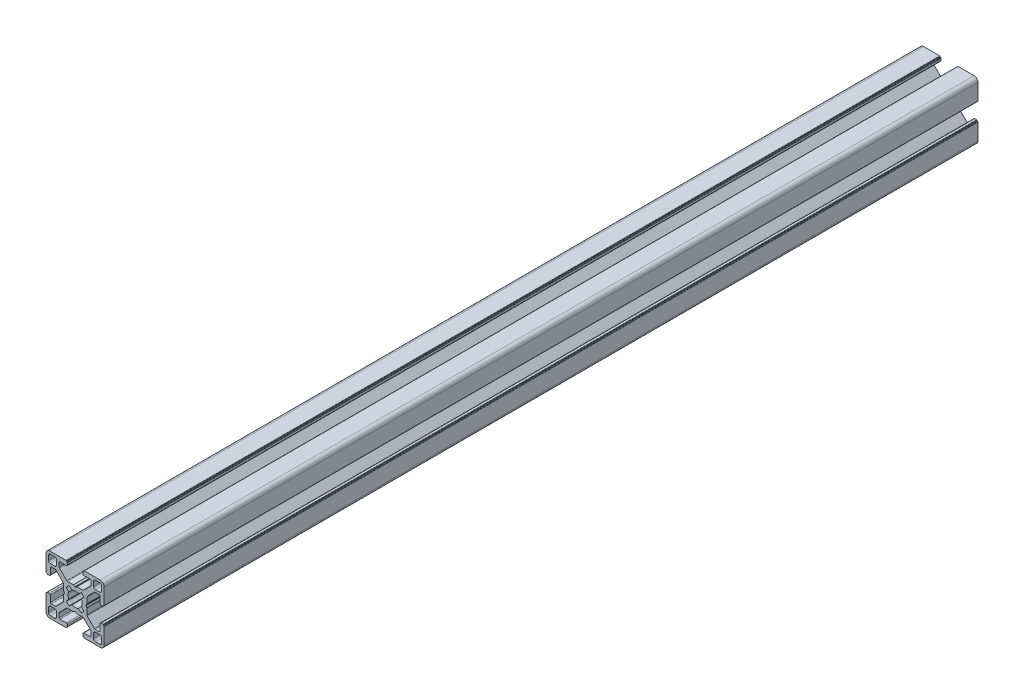
SolidWorks part; units mm, degrees
ref_plane "Alzado" through (0, 0, 0) normal (0, 0, 1) x (1, 0, 0)
ref_plane "Planta" through (0, 0, 0) normal (0, 1, 0) x (1, 0, 0)
ref_plane "Vista lateral" through (0, 0, 0) normal (1, 0, 0) x (0, 0, -1)
ref_plane "Plano1" through (0, 0, 1000) normal (0, 0, 1) x (1, 0, 0)
sketch "Croquis1" plane through (0, 0, 1000) normal (0, 0, 1) x (1, 0, 0)
  line L0 (8, -5.5) -> (5.8, -5.5)
  line L1 (4.8, -4.5) -> (4.8, -2.3)
  line L2 (5.8, -1.3) -> (8, -1.3)
  line L3 (9, -2.3) -> (9, -4.5)
  line L4 (-15.2, -5.5) -> (-17.4, -5.5)
  line L5 (-18.4, -4.5) -> (-18.4, -2.3)
  line L6 (-17.4, -1.3) -> (-15.2, -1.3)
  line L7 (-14.2, -2.3) -> (-14.2, -4.5)
  line L8 (-17.4, -24.5) -> (-15.2, -24.5)
  line L9 (-14.2, -25.5) -> (-14.2, -27.7)
  line L10 (-15.2, -28.7) -> (-17.4, -28.7)
  line L11 (-18.4, -27.7) -> (-18.4, -25.5)
  line L12 (5.8, -24.5) -> (8, -24.5)
  line L13 (9, -25.5) -> (9, -27.7)
  line L14 (8, -28.7) -> (5.8, -28.7)
  line L15 (4.8, -27.7) -> (4.8, -25.5)
  line L16 (-7.8359, -10.4816) -> (-6.3001, -11.7194)
  line L17 (-3.0999, -11.7194) -> (-1.5641, -10.4816)
  line L18 (-0.1947, -11.8453) -> (-1.4194, -13.3999)
  line L19 (-1.4194, -16.6001) -> (-0.1947, -18.1547)
  line L20 (-1.5641, -19.5184) -> (-3.0999, -18.2806)
  line L21 (-6.3001, -18.2806) -> (-7.8359, -19.5184)
  line L22 (-9.2053, -18.1547) -> (-7.9806, -16.6001)
  line L23 (-7.9806, -13.3999) -> (-9.2053, -11.8453)
  line L24 (9.8, -10.5) -> (10.1, -10.5)
  line L25 (10.3, -10.3) -> (10.3, -2)
  line L26 (8.3, 0) -> (0, 0)
  line L27 (-0.2, -0.2) -> (-0.2, -0.5)
  line L28 (-0.2, -0.5) -> (-0.5, -0.5)
  line L29 (-0.7, -0.7) -> (-0.7, -1.7)
  line L30 (-0.2, -2.2) -> (3.05, -2.2)
  line L31 (3.55, -2.7) -> (3.55, -4.7431)
  line L32 (3.4037, -5.0964) -> (-0.3491, -8.8534)
  line L33 (-0.7028, -9) -> (-3.7468, -9)
  line L34 (-3.8462, -9.0264) -> (-4.6006, -9.4583)
  line L35 (-4.7994, -9.4583) -> (-5.5538, -9.0264)
  line L36 (-5.6532, -9) -> (-8.6972, -9)
  line L37 (-9.0509, -8.8534) -> (-12.8037, -5.0964)
  line L38 (-12.95, -4.7431) -> (-12.95, -2.7)
  line L39 (-12.45, -2.2) -> (-9.2, -2.2)
  line L40 (-8.7, -1.7) -> (-8.7, -0.7)
  line L41 (-8.9, -0.5) -> (-9.2, -0.5)
  line L42 (-9.2, -0.5) -> (-9.2, -0.2)
  line L43 (-9.4, 0) -> (-17.7, 0)
  line L44 (-19.7, -2) -> (-19.7, -10.3)
  line L45 (-19.5, -10.5) -> (-19.2, -10.5)
  line L46 (-19.2, -10.5) -> (-19.2, -10.8)
  line L47 (-19, -11) -> (-18, -11)
  line L48 (-17.5, -10.5) -> (-17.5, -7.25)
  line L49 (-17, -6.75) -> (-14.9569, -6.75)
  line L50 (-14.6036, -6.8963) -> (-10.8466, -10.6491)
  line L51 (-10.7, -11.0028) -> (-10.7, -14.0468)
  line L52 (-10.6736, -14.1462) -> (-10.2417, -14.9006)
  line L53 (-10.2417, -15.0994) -> (-10.6736, -15.8538)
  line L54 (-10.7, -15.9532) -> (-10.7, -18.9972)
  line L55 (-10.8466, -19.3509) -> (-14.6036, -23.1037)
  line L56 (-14.9569, -23.25) -> (-17, -23.25)
  line L57 (-17.5, -22.75) -> (-17.5, -19.5)
  line L58 (-18, -19) -> (-19, -19)
  line L59 (-19.2, -19.2) -> (-19.2, -19.5)
  line L60 (-19.2, -19.5) -> (-19.5, -19.5)
  line L61 (-19.7, -19.7) -> (-19.7, -28)
  line L62 (-17.7, -30) -> (-9.4, -30)
  line L63 (-9.2, -29.8) -> (-9.2, -29.5)
  line L64 (-9.2, -29.5) -> (-8.9, -29.5)
  line L65 (-8.7, -29.3) -> (-8.7, -28.3)
  line L66 (-9.2, -27.8) -> (-12.45, -27.8)
  line L67 (-12.95, -27.3) -> (-12.95, -25.2569)
  line L68 (-12.8037, -24.9036) -> (-9.0509, -21.1466)
  line L69 (-8.6972, -21) -> (-5.6532, -21)
  line L70 (-5.5538, -20.9736) -> (-4.7994, -20.5417)
  line L71 (-4.6006, -20.5417) -> (-3.8462, -20.9736)
  line L72 (-3.7468, -21) -> (-0.7028, -21)
  line L73 (-0.3491, -21.1466) -> (3.4037, -24.9036)
  line L74 (3.55, -25.2569) -> (3.55, -27.3)
  line L75 (3.05, -27.8) -> (-0.2, -27.8)
  line L76 (-0.7, -28.3) -> (-0.7, -29.3)
  line L77 (-0.5, -29.5) -> (-0.2, -29.5)
  line L78 (-0.2, -29.5) -> (-0.2, -29.8)
  line L79 (0, -30) -> (8.3, -30)
  line L80 (10.3, -28) -> (10.3, -19.7)
  line L81 (10.1, -19.5) -> (9.8, -19.5)
  line L82 (9.8, -19.5) -> (9.8, -19.2)
  line L83 (9.6, -19) -> (8.6, -19)
  line L84 (8.1, -19.5) -> (8.1, -22.75)
  line L85 (7.6, -23.25) -> (5.5569, -23.25)
  line L86 (5.2036, -23.1037) -> (1.4466, -19.3509)
  line L87 (1.3, -18.9972) -> (1.3, -15.9532)
  line L88 (1.2736, -15.8538) -> (0.8417, -15.0994)
  line L89 (0.8417, -14.9006) -> (1.2736, -14.1462)
  line L90 (1.3, -14.0468) -> (1.3, -11.0028)
  line L91 (1.4466, -10.6491) -> (5.2036, -6.8963)
  line L92 (5.5569, -6.75) -> (7.6, -6.75)
  line L93 (8.1, -7.25) -> (8.1, -10.5)
  line L94 (8.6, -11) -> (9.6, -11)
  line L95 (9.8, -10.8) -> (9.8, -10.5)
  arc A0 (9, -4.5) -> (8, -5.5) centre (8, -4.5) cw
  arc A1 (5.8, -5.5) -> (4.8, -4.5) centre (5.8, -4.5) cw
  arc A2 (4.8, -2.3) -> (5.8, -1.3) centre (5.8, -2.3) cw
  arc A3 (8, -1.3) -> (9, -2.3) centre (8, -2.3) cw
  arc A4 (-14.2, -4.5) -> (-15.2, -5.5) centre (-15.2, -4.5) cw
  arc A5 (-17.4, -5.5) -> (-18.4, -4.5) centre (-17.4, -4.5) cw
  arc A6 (-18.4, -2.3) -> (-17.4, -1.3) centre (-17.4, -2.3) cw
  arc A7 (-15.2, -1.3) -> (-14.2, -2.3) centre (-15.2, -2.3) cw
  arc A8 (-18.4, -25.5) -> (-17.4, -24.5) centre (-17.4, -25.5) cw
  arc A9 (-15.2, -24.5) -> (-14.2, -25.5) centre (-15.2, -25.5) cw
  arc A10 (-14.2, -27.7) -> (-15.2, -28.7) centre (-15.2, -27.7) cw
  arc A11 (-17.4, -28.7) -> (-18.4, -27.7) centre (-17.4, -27.7) cw
  arc A12 (4.8, -25.5) -> (5.8, -24.5) centre (5.8, -25.5) cw
  arc A13 (8, -24.5) -> (9, -25.5) centre (8, -25.5) cw
  arc A14 (9, -27.7) -> (8, -28.7) centre (8, -27.7) cw
  arc A15 (5.8, -28.7) -> (4.8, -27.7) centre (5.8, -27.7) cw
  arc A16 (-9.2053, -11.8453) -> (-7.8359, -10.4816) centre (-4.7, -15) cw
  arc A17 (-6.3001, -11.7194) -> (-3.0999, -11.7194) centre (-4.7, -15) cw
  arc A18 (-1.5641, -10.4816) -> (-0.1947, -11.8453) centre (-4.7, -15) cw
  arc A19 (-1.4194, -13.3999) -> (-1.4194, -16.6001) centre (-4.7, -15) cw
  arc A20 (-0.1947, -18.1547) -> (-1.5641, -19.5184) centre (-4.7, -15) cw
  arc A21 (-3.0999, -18.2806) -> (-6.3001, -18.2806) centre (-4.7, -15) cw
  arc A22 (-7.8359, -19.5184) -> (-9.2053, -18.1547) centre (-4.7, -15) cw
  arc A23 (-7.9806, -16.6001) -> (-7.9806, -13.3999) centre (-4.7, -15) cw
  arc A24 (10.1, -10.5) -> (10.3, -10.3) centre (10.1, -10.3) ccw
  arc A25 (10.3, -2) -> (8.3, 0) centre (8.3, -2) ccw
  arc A26 (0, 0) -> (-0.2, -0.2) centre (0, -0.2) ccw
  arc A27 (-0.5, -0.5) -> (-0.7, -0.7) centre (-0.5, -0.7) ccw
  arc A28 (-0.7, -1.7) -> (-0.2, -2.2) centre (-0.2, -1.7) ccw
  arc A29 (3.05, -2.2) -> (3.55, -2.7) centre (3.05, -2.7) cw
  arc A30 (3.55, -4.7431) -> (3.4037, -5.0964) centre (3.05, -4.7431) cw
  arc A31 (-0.3491, -8.8534) -> (-0.7028, -9) centre (-0.7028, -8.5) cw
  arc A32 (-3.7468, -9) -> (-3.8462, -9.0264) centre (-3.7468, -9.2) ccw
  arc A33 (-4.6006, -9.4583) -> (-4.7994, -9.4583) centre (-4.7, -9.2847) cw
  arc A34 (-5.5538, -9.0264) -> (-5.6532, -9) centre (-5.6532, -9.2) ccw
  arc A35 (-8.6972, -9) -> (-9.0509, -8.8534) centre (-8.6972, -8.5) cw
  arc A36 (-12.8037, -5.0964) -> (-12.95, -4.7431) centre (-12.45, -4.7431) cw
  arc A37 (-12.95, -2.7) -> (-12.45, -2.2) centre (-12.45, -2.7) cw
  arc A38 (-9.2, -2.2) -> (-8.7, -1.7) centre (-9.2, -1.7) ccw
  arc A39 (-8.7, -0.7) -> (-8.9, -0.5) centre (-8.9, -0.7) ccw
  arc A40 (-9.2, -0.2) -> (-9.4, 0) centre (-9.4, -0.2) ccw
  arc A41 (-17.7, 0) -> (-19.7, -2) centre (-17.7, -2) ccw
  arc A42 (-19.7, -10.3) -> (-19.5, -10.5) centre (-19.5, -10.3) ccw
  arc A43 (-19.2, -10.8) -> (-19, -11) centre (-19, -10.8) ccw
  arc A44 (-18, -11) -> (-17.5, -10.5) centre (-18, -10.5) ccw
  arc A45 (-17.5, -7.25) -> (-17, -6.75) centre (-17, -7.25) cw
  arc A46 (-14.9569, -6.75) -> (-14.6036, -6.8963) centre (-14.9569, -7.25) cw
  arc A47 (-10.8466, -10.6491) -> (-10.7, -11.0028) centre (-11.2, -11.0028) cw
  arc A48 (-10.7, -14.0468) -> (-10.6736, -14.1462) centre (-10.5, -14.0468) ccw
  arc A49 (-10.2417, -14.9006) -> (-10.2417, -15.0994) centre (-10.4153, -15) cw
  arc A50 (-10.6736, -15.8538) -> (-10.7, -15.9532) centre (-10.5, -15.9532) ccw
  arc A51 (-10.7, -18.9972) -> (-10.8466, -19.3509) centre (-11.2, -18.9972) cw
  arc A52 (-14.6036, -23.1037) -> (-14.9569, -23.25) centre (-14.9569, -22.75) cw
  arc A53 (-17, -23.25) -> (-17.5, -22.75) centre (-17, -22.75) cw
  arc A54 (-17.5, -19.5) -> (-18, -19) centre (-18, -19.5) ccw
  arc A55 (-19, -19) -> (-19.2, -19.2) centre (-19, -19.2) ccw
  arc A56 (-19.5, -19.5) -> (-19.7, -19.7) centre (-19.5, -19.7) ccw
  arc A57 (-19.7, -28) -> (-17.7, -30) centre (-17.7, -28) ccw
  arc A58 (-9.4, -30) -> (-9.2, -29.8) centre (-9.4, -29.8) ccw
  arc A59 (-8.9, -29.5) -> (-8.7, -29.3) centre (-8.9, -29.3) ccw
  arc A60 (-8.7, -28.3) -> (-9.2, -27.8) centre (-9.2, -28.3) ccw
  arc A61 (-12.45, -27.8) -> (-12.95, -27.3) centre (-12.45, -27.3) cw
  arc A62 (-12.95, -25.2569) -> (-12.8037, -24.9036) centre (-12.45, -25.2569) cw
  arc A63 (-9.0509, -21.1466) -> (-8.6972, -21) centre (-8.6972, -21.5) cw
  arc A64 (-5.6532, -21) -> (-5.5538, -20.9736) centre (-5.6532, -20.8) ccw
  arc A65 (-4.7994, -20.5417) -> (-4.6006, -20.5417) centre (-4.7, -20.7153) cw
  arc A66 (-3.8462, -20.9736) -> (-3.7468, -21) centre (-3.7468, -20.8) ccw
  arc A67 (-0.7028, -21) -> (-0.3491, -21.1466) centre (-0.7028, -21.5) cw
  arc A68 (3.4037, -24.9036) -> (3.55, -25.2569) centre (3.05, -25.2569) cw
  arc A69 (3.55, -27.3) -> (3.05, -27.8) centre (3.05, -27.3) cw
  arc A70 (-0.2, -27.8) -> (-0.7, -28.3) centre (-0.2, -28.3) ccw
  arc A71 (-0.7, -29.3) -> (-0.5, -29.5) centre (-0.5, -29.3) ccw
  arc A72 (-0.2, -29.8) -> (0, -30) centre (0, -29.8) ccw
  arc A73 (8.3, -30) -> (10.3, -28) centre (8.3, -28) ccw
  arc A74 (10.3, -19.7) -> (10.1, -19.5) centre (10.1, -19.7) ccw
  arc A75 (9.8, -19.2) -> (9.6, -19) centre (9.6, -19.2) ccw
  arc A76 (8.6, -19) -> (8.1, -19.5) centre (8.6, -19.5) ccw
  arc A77 (8.1, -22.75) -> (7.6, -23.25) centre (7.6, -22.75) cw
  arc A78 (5.5569, -23.25) -> (5.2036, -23.1037) centre (5.5569, -22.75) cw
  arc A79 (1.4466, -19.3509) -> (1.3, -18.9972) centre (1.8, -18.9972) cw
  arc A80 (1.3, -15.9532) -> (1.2736, -15.8538) centre (1.1, -15.9532) ccw
  arc A81 (0.8417, -15.0994) -> (0.8417, -14.9006) centre (1.0153, -15) cw
  arc A82 (1.2736, -14.1462) -> (1.3, -14.0468) centre (1.1, -14.0468) ccw
  arc A83 (1.3, -11.0028) -> (1.4466, -10.6491) centre (1.8, -11.0028) cw
  arc A84 (5.2036, -6.8963) -> (5.5569, -6.75) centre (5.5569, -7.25) cw
  arc A85 (7.6, -6.75) -> (8.1, -7.25) centre (7.6, -7.25) cw
  arc A86 (8.1, -10.5) -> (8.6, -11) centre (8.6, -10.5) ccw
  arc A87 (9.6, -11) -> (9.8, -10.8) centre (9.6, -10.8) ccw
extrude "Saliente-Extruir1" add sketch "Croquis1" against normal blind 1000
sketch "Croquis4" plane through (0, 0, 0) normal (0, 0, -1) x (-1, 0, 0)
  line L72 (-9.8, -10.5) -> (-9.8, -10.8)
  line L73 (-9.6, -11) -> (-8.6, -11)
  line L74 (-8.1, -10.5) -> (-8.1, -7.25)
  line L75 (-7.6, -6.75) -> (-5.5569, -6.75)
  line L76 (-5.2036, -6.8963) -> (-1.4466, -10.6491)
  line L77 (-1.3, -11.0028) -> (-1.3, -14.0468)
  line L78 (-1.2736, -14.1462) -> (-0.8417, -14.9006)
  line L79 (-0.8417, -15.0994) -> (-1.2736, -15.8538)
  line L80 (-1.3, -15.9532) -> (-1.3, -18.9972)
  line L81 (-1.4466, -19.3509) -> (-5.2036, -23.1037)
  line L82 (-5.5569, -23.25) -> (-7.6, -23.25)
  line L83 (-8.1, -22.75) -> (-8.1, -19.5)
  line L84 (-8.6, -19) -> (-9.6, -19)
  line L85 (-9.8, -19.2) -> (-9.8, -19.5)
  line L86 (-9.8, -19.5) -> (-10.1, -19.5)
  line L87 (-10.3, -19.7) -> (-10.3, -28)
  line L88 (-8.3, -30) -> (0, -30)
  line L89 (0.2, -29.8) -> (0.2, -29.5)
  line L90 (0.2, -29.5) -> (0.5, -29.5)
  line L91 (0.7, -29.3) -> (0.7, -28.3)
  line L92 (0.2, -27.8) -> (-3.05, -27.8)
  line L93 (-3.55, -27.3) -> (-3.55, -25.2569)
  line L94 (-3.4037, -24.9036) -> (0.3491, -21.1466)
  line L95 (0.7028, -21) -> (3.7468, -21)
  line L96 (3.8462, -20.9736) -> (4.6006, -20.5417)
  line L97 (4.7994, -20.5417) -> (5.5538, -20.9736)
  line L98 (5.6532, -21) -> (8.6972, -21)
  line L99 (9.0509, -21.1466) -> (12.8037, -24.9036)
  line L100 (12.95, -25.2569) -> (12.95, -27.3)
  line L101 (12.45, -27.8) -> (9.2, -27.8)
  line L102 (8.7, -28.3) -> (8.7, -29.3)
  line L103 (8.9, -29.5) -> (9.2, -29.5)
  line L104 (9.2, -29.5) -> (9.2, -29.8)
  line L105 (9.4, -30) -> (17.7, -30)
  line L106 (19.7, -28) -> (19.7, -19.7)
  line L107 (19.5, -19.5) -> (19.2, -19.5)
  line L108 (19.2, -19.5) -> (19.2, -19.2)
  line L109 (19, -19) -> (18, -19)
  line L110 (17.5, -19.5) -> (17.5, -22.75)
  line L111 (17, -23.25) -> (14.9569, -23.25)
  line L112 (14.6036, -23.1037) -> (10.8466, -19.3509)
  line L113 (10.7, -18.9972) -> (10.7, -15.9532)
  line L114 (10.6736, -15.8538) -> (10.2417, -15.0994)
  line L115 (10.2417, -14.9006) -> (10.6736, -14.1462)
  line L116 (10.7, -14.0468) -> (10.7, -11.0028)
  line L117 (10.8466, -10.6491) -> (14.6036, -6.8963)
  line L118 (14.9569, -6.75) -> (17, -6.75)
  line L119 (17.5, -7.25) -> (17.5, -10.5)
  line L120 (18, -11) -> (19, -11)
  line L121 (19.2, -10.8) -> (19.2, -10.5)
  line L122 (19.2, -10.5) -> (19.5, -10.5)
  line L123 (19.7, -10.3) -> (19.7, -2)
  line L124 (17.7, 0) -> (9.4, 0)
  line L125 (9.2, -0.2) -> (9.2, -0.5)
  line L126 (9.2, -0.5) -> (8.9, -0.5)
  line L127 (8.7, -0.7) -> (8.7, -1.7)
  line L128 (9.2, -2.2) -> (12.45, -2.2)
  line L129 (12.95, -2.7) -> (12.95, -4.7431)
  line L130 (12.8037, -5.0964) -> (9.0509, -8.8534)
  line L131 (8.6972, -9) -> (5.6532, -9)
  line L132 (5.5538, -9.0264) -> (4.7994, -9.4583)
  line L133 (4.6006, -9.4583) -> (3.8462, -9.0264)
  line L134 (3.7468, -9) -> (0.7028, -9)
  line L135 (0.3491, -8.8534) -> (-3.4037, -5.0964)
  line L136 (-3.55, -4.7431) -> (-3.55, -2.7)
  line L137 (-3.05, -2.2) -> (0.2, -2.2)
  line L138 (0.7, -1.7) -> (0.7, -0.7)
  line L139 (0.5, -0.5) -> (0.2, -0.5)
  line L140 (0.2, -0.5) -> (0.2, -0.2)
  line L141 (0, 0) -> (-8.3, 0)
  line L142 (-10.3, -2) -> (-10.3, -10.3)
  line L143 (-10.1, -10.5) -> (-9.8, -10.5)
  line L144 (-9.8, -10.5) -> (-9.8, -10.8)
  line L145 (-9.6, -11) -> (-8.6, -11)
  line L146 (-8.1, -10.5) -> (-8.1, -7.25)
  line L147 (-7.6, -6.75) -> (-5.5569, -6.75)
  line L148 (-5.2036, -6.8963) -> (-1.4466, -10.6491)
  line L149 (-1.3, -11.0028) -> (-1.3, -14.0468)
  line L150 (-1.2736, -14.1462) -> (-0.8417, -14.9006)
  line L151 (-0.8417, -15.0994) -> (-1.2736, -15.8538)
  line L152 (-1.3, -15.9532) -> (-1.3, -18.9972)
  line L153 (-1.4466, -19.3509) -> (-5.2036, -23.1037)
  line L154 (-5.5569, -23.25) -> (-7.6, -23.25)
  line L155 (-8.1, -22.75) -> (-8.1, -19.5)
  line L156 (-8.6, -19) -> (-9.6, -19)
  line L157 (-9.8, -19.2) -> (-9.8, -19.5)
  line L158 (-9.8, -19.5) -> (-10.1, -19.5)
  line L159 (-10.3, -19.7) -> (-10.3, -28)
  line L160 (-8.3, -30) -> (0, -30)
  line L161 (0.2, -29.8) -> (0.2, -29.5)
  line L162 (0.2, -29.5) -> (0.5, -29.5)
  line L163 (0.7, -29.3) -> (0.7, -28.3)
  line L164 (0.2, -27.8) -> (-3.05, -27.8)
  line L165 (-3.55, -27.3) -> (-3.55, -25.2569)
  line L166 (-3.4037, -24.9036) -> (0.3491, -21.1466)
  line L167 (0.7028, -21) -> (3.7468, -21)
  line L168 (3.8462, -20.9736) -> (4.6006, -20.5417)
  line L169 (4.7994, -20.5417) -> (5.5538, -20.9736)
  line L170 (5.6532, -21) -> (8.6972, -21)
  line L171 (9.0509, -21.1466) -> (12.8037, -24.9036)
  line L172 (12.95, -25.2569) -> (12.95, -27.3)
  line L173 (12.45, -27.8) -> (9.2, -27.8)
  line L174 (8.7, -28.3) -> (8.7, -29.3)
  line L175 (8.9, -29.5) -> (9.2, -29.5)
  line L176 (9.2, -29.5) -> (9.2, -29.8)
  line L177 (9.4, -30) -> (17.7, -30)
  line L178 (19.7, -28) -> (19.7, -19.7)
  line L179 (19.5, -19.5) -> (19.2, -19.5)
  line L180 (19.2, -19.5) -> (19.2, -19.2)
  line L181 (19, -19) -> (18, -19)
  line L182 (17.5, -19.5) -> (17.5, -22.75)
  line L183 (17, -23.25) -> (14.9569, -23.25)
  line L184 (14.6036, -23.1037) -> (10.8466, -19.3509)
  line L185 (10.7, -18.9972) -> (10.7, -15.9532)
  line L186 (10.6736, -15.8538) -> (10.2417, -15.0994)
  line L187 (10.2417, -14.9006) -> (10.6736, -14.1462)
  line L188 (10.7, -14.0468) -> (10.7, -11.0028)
  line L189 (10.8466, -10.6491) -> (14.6036, -6.8963)
  line L190 (14.9569, -6.75) -> (17, -6.75)
  line L191 (17.5, -7.25) -> (17.5, -10.5)
  line L192 (18, -11) -> (19, -11)
  line L193 (19.2, -10.8) -> (19.2, -10.5)
  line L194 (19.2, -10.5) -> (19.5, -10.5)
  line L195 (19.7, -10.3) -> (19.7, -2)
  line L196 (17.7, 0) -> (9.4, 0)
  line L197 (9.2, -0.2) -> (9.2, -0.5)
  line L198 (9.2, -0.5) -> (8.9, -0.5)
  line L199 (8.7, -0.7) -> (8.7, -1.7)
  line L200 (9.2, -2.2) -> (12.45, -2.2)
  line L201 (12.95, -2.7) -> (12.95, -4.7431)
  line L202 (12.8037, -5.0964) -> (9.0509, -8.8534)
  line L203 (8.6972, -9) -> (5.6532, -9)
  line L204 (5.5538, -9.0264) -> (4.7994, -9.4583)
  line L205 (4.6006, -9.4583) -> (3.8462, -9.0264)
  line L206 (3.7468, -9) -> (0.7028, -9)
  line L207 (0.3491, -8.8534) -> (-3.4037, -5.0964)
  line L208 (-3.55, -4.7431) -> (-3.55, -2.7)
  line L209 (-3.05, -2.2) -> (0.2, -2.2)
  line L210 (0.7, -1.7) -> (0.7, -0.7)
  line L211 (0.5, -0.5) -> (0.2, -0.5)
  line L212 (0.2, -0.5) -> (0.2, -0.2)
  line L213 (0, 0) -> (-8.3, 0)
  line L214 (-10.3, -2) -> (-10.3, -10.3)
  line L215 (-10.1, -10.5) -> (-9.8, -10.5)
  arc A64 (-9.8, -10.8) -> (-9.6, -11) centre (-9.6, -10.8) ccw
  arc A65 (-8.6, -11) -> (-8.1, -10.5) centre (-8.6, -10.5) ccw
  arc A66 (-7.6, -6.75) -> (-8.1, -7.25) centre (-7.6, -7.25) ccw
  arc A67 (-5.2036, -6.8963) -> (-5.5569, -6.75) centre (-5.5569, -7.25) ccw
  arc A68 (-1.3, -11.0028) -> (-1.4466, -10.6491) centre (-1.8, -11.0028) ccw
  arc A69 (-1.3, -14.0468) -> (-1.2736, -14.1462) centre (-1.1, -14.0468) ccw
  arc A70 (-0.8417, -15.0994) -> (-0.8417, -14.9006) centre (-1.0153, -15) ccw
  arc A71 (-1.2736, -15.8538) -> (-1.3, -15.9532) centre (-1.1, -15.9532) ccw
  arc A72 (-1.4466, -19.3509) -> (-1.3, -18.9972) centre (-1.8, -18.9972) ccw
  arc A73 (-5.5569, -23.25) -> (-5.2036, -23.1037) centre (-5.5569, -22.75) ccw
  arc A74 (-8.1, -22.75) -> (-7.6, -23.25) centre (-7.6, -22.75) ccw
  arc A75 (-8.1, -19.5) -> (-8.6, -19) centre (-8.6, -19.5) ccw
  arc A76 (-9.6, -19) -> (-9.8, -19.2) centre (-9.6, -19.2) ccw
  arc A77 (-10.1, -19.5) -> (-10.3, -19.7) centre (-10.1, -19.7) ccw
  arc A78 (-10.3, -28) -> (-8.3, -30) centre (-8.3, -28) ccw
  arc A79 (0, -30) -> (0.2, -29.8) centre (0, -29.8) ccw
  arc A80 (0.5, -29.5) -> (0.7, -29.3) centre (0.5, -29.3) ccw
  arc A81 (0.7, -28.3) -> (0.2, -27.8) centre (0.2, -28.3) ccw
  arc A82 (-3.55, -27.3) -> (-3.05, -27.8) centre (-3.05, -27.3) ccw
  arc A83 (-3.4037, -24.9036) -> (-3.55, -25.2569) centre (-3.05, -25.2569) ccw
  arc A84 (0.7028, -21) -> (0.3491, -21.1466) centre (0.7028, -21.5) ccw
  arc A85 (3.7468, -21) -> (3.8462, -20.9736) centre (3.7468, -20.8) ccw
  arc A86 (4.7994, -20.5417) -> (4.6006, -20.5417) centre (4.7, -20.7153) ccw
  arc A87 (5.5538, -20.9736) -> (5.6532, -21) centre (5.6532, -20.8) ccw
  arc A88 (9.0509, -21.1466) -> (8.6972, -21) centre (8.6972, -21.5) ccw
  arc A89 (12.95, -25.2569) -> (12.8037, -24.9036) centre (12.45, -25.2569) ccw
  arc A90 (12.45, -27.8) -> (12.95, -27.3) centre (12.45, -27.3) ccw
  arc A91 (9.2, -27.8) -> (8.7, -28.3) centre (9.2, -28.3) ccw
  arc A92 (8.7, -29.3) -> (8.9, -29.5) centre (8.9, -29.3) ccw
  arc A93 (9.2, -29.8) -> (9.4, -30) centre (9.4, -29.8) ccw
  arc A94 (17.7, -30) -> (19.7, -28) centre (17.7, -28) ccw
  arc A95 (19.7, -19.7) -> (19.5, -19.5) centre (19.5, -19.7) ccw
  arc A96 (19.2, -19.2) -> (19, -19) centre (19, -19.2) ccw
  arc A97 (18, -19) -> (17.5, -19.5) centre (18, -19.5) ccw
  arc A98 (17, -23.25) -> (17.5, -22.75) centre (17, -22.75) ccw
  arc A99 (14.6036, -23.1037) -> (14.9569, -23.25) centre (14.9569, -22.75) ccw
  arc A100 (10.7, -18.9972) -> (10.8466, -19.3509) centre (11.2, -18.9972) ccw
  arc A101 (10.7, -15.9532) -> (10.6736, -15.8538) centre (10.5, -15.9532) ccw
  arc A102 (10.2417, -14.9006) -> (10.2417, -15.0994) centre (10.4153, -15) ccw
  arc A103 (10.6736, -14.1462) -> (10.7, -14.0468) centre (10.5, -14.0468) ccw
  arc A104 (10.8466, -10.6491) -> (10.7, -11.0028) centre (11.2, -11.0028) ccw
  arc A105 (14.9569, -6.75) -> (14.6036, -6.8963) centre (14.9569, -7.25) ccw
  arc A106 (17.5, -7.25) -> (17, -6.75) centre (17, -7.25) ccw
  arc A107 (17.5, -10.5) -> (18, -11) centre (18, -10.5) ccw
  arc A108 (19, -11) -> (19.2, -10.8) centre (19, -10.8) ccw
  arc A109 (19.5, -10.5) -> (19.7, -10.3) centre (19.5, -10.3) ccw
  arc A110 (19.7, -2) -> (17.7, 0) centre (17.7, -2) ccw
  arc A111 (9.4, 0) -> (9.2, -0.2) centre (9.4, -0.2) ccw
  arc A112 (8.9, -0.5) -> (8.7, -0.7) centre (8.9, -0.7) ccw
  arc A113 (8.7, -1.7) -> (9.2, -2.2) centre (9.2, -1.7) ccw
  arc A114 (12.95, -2.7) -> (12.45, -2.2) centre (12.45, -2.7) ccw
  arc A115 (12.8037, -5.0964) -> (12.95, -4.7431) centre (12.45, -4.7431) ccw
  arc A116 (8.6972, -9) -> (9.0509, -8.8534) centre (8.6972, -8.5) ccw
  arc A117 (5.6532, -9) -> (5.5538, -9.0264) centre (5.6532, -9.2) ccw
  arc A118 (4.6006, -9.4583) -> (4.7994, -9.4583) centre (4.7, -9.2847) ccw
  arc A119 (3.8462, -9.0264) -> (3.7468, -9) centre (3.7468, -9.2) ccw
  arc A120 (0.3491, -8.8534) -> (0.7028, -9) centre (0.7028, -8.5) ccw
  arc A121 (-3.55, -4.7431) -> (-3.4037, -5.0964) centre (-3.05, -4.7431) ccw
  arc A122 (-3.05, -2.2) -> (-3.55, -2.7) centre (-3.05, -2.7) ccw
  arc A123 (0.2, -2.2) -> (0.7, -1.7) centre (0.2, -1.7) ccw
  arc A124 (0.7, -0.7) -> (0.5, -0.5) centre (0.5, -0.7) ccw
  arc A125 (0.2, -0.2) -> (0, 0) centre (0, -0.2) ccw
  arc A126 (-8.3, 0) -> (-10.3, -2) centre (-8.3, -2) ccw
  arc A127 (-10.3, -10.3) -> (-10.1, -10.5) centre (-10.1, -10.3) ccw
  arc A128 (-9.8, -10.8) -> (-9.6, -11) centre (-9.6, -10.8) ccw
  arc A129 (-8.6, -11) -> (-8.1, -10.5) centre (-8.6, -10.5) ccw
  arc A130 (-7.6, -6.75) -> (-8.1, -7.25) centre (-7.6, -7.25) ccw
  arc A131 (-5.2036, -6.8963) -> (-5.5569, -6.75) centre (-5.5569, -7.25) ccw
  arc A132 (-1.3, -11.0028) -> (-1.4466, -10.6491) centre (-1.8, -11.0028) ccw
  arc A133 (-1.3, -14.0468) -> (-1.2736, -14.1462) centre (-1.1, -14.0468) ccw
  arc A134 (-0.8417, -15.0994) -> (-0.8417, -14.9006) centre (-1.0153, -15) ccw
  arc A135 (-1.2736, -15.8538) -> (-1.3, -15.9532) centre (-1.1, -15.9532) ccw
  arc A136 (-1.4466, -19.3509) -> (-1.3, -18.9972) centre (-1.8, -18.9972) ccw
  arc A137 (-5.5569, -23.25) -> (-5.2036, -23.1037) centre (-5.5569, -22.75) ccw
  arc A138 (-8.1, -22.75) -> (-7.6, -23.25) centre (-7.6, -22.75) ccw
  arc A139 (-8.1, -19.5) -> (-8.6, -19) centre (-8.6, -19.5) ccw
  arc A140 (-9.6, -19) -> (-9.8, -19.2) centre (-9.6, -19.2) ccw
  arc A141 (-10.1, -19.5) -> (-10.3, -19.7) centre (-10.1, -19.7) ccw
  arc A142 (-10.3, -28) -> (-8.3, -30) centre (-8.3, -28) ccw
  arc A143 (0, -30) -> (0.2, -29.8) centre (0, -29.8) ccw
  arc A144 (0.5, -29.5) -> (0.7, -29.3) centre (0.5, -29.3) ccw
  arc A145 (0.7, -28.3) -> (0.2, -27.8) centre (0.2, -28.3) ccw
  arc A146 (-3.55, -27.3) -> (-3.05, -27.8) centre (-3.05, -27.3) ccw
  arc A147 (-3.4037, -24.9036) -> (-3.55, -25.2569) centre (-3.05, -25.2569) ccw
  arc A148 (0.7028, -21) -> (0.3491, -21.1466) centre (0.7028, -21.5) ccw
  arc A149 (3.7468, -21) -> (3.8462, -20.9736) centre (3.7468, -20.8) ccw
  arc A150 (4.7994, -20.5417) -> (4.6006, -20.5417) centre (4.7, -20.7153) ccw
  arc A151 (5.5538, -20.9736) -> (5.6532, -21) centre (5.6532, -20.8) ccw
  arc A152 (9.0509, -21.1466) -> (8.6972, -21) centre (8.6972, -21.5) ccw
  arc A153 (12.95, -25.2569) -> (12.8037, -24.9036) centre (12.45, -25.2569) ccw
  arc A154 (12.45, -27.8) -> (12.95, -27.3) centre (12.45, -27.3) ccw
  arc A155 (9.2, -27.8) -> (8.7, -28.3) centre (9.2, -28.3) ccw
  arc A156 (8.7, -29.3) -> (8.9, -29.5) centre (8.9, -29.3) ccw
  arc A157 (9.2, -29.8) -> (9.4, -30) centre (9.4, -29.8) ccw
  arc A158 (17.7, -30) -> (19.7, -28) centre (17.7, -28) ccw
  arc A159 (19.7, -19.7) -> (19.5, -19.5) centre (19.5, -19.7) ccw
  arc A160 (19.2, -19.2) -> (19, -19) centre (19, -19.2) ccw
  arc A161 (18, -19) -> (17.5, -19.5) centre (18, -19.5) ccw
  arc A162 (17, -23.25) -> (17.5, -22.75) centre (17, -22.75) ccw
  arc A163 (14.6036, -23.1037) -> (14.9569, -23.25) centre (14.9569, -22.75) ccw
  arc A164 (10.7, -18.9972) -> (10.8466, -19.3509) centre (11.2, -18.9972) ccw
  arc A165 (10.7, -15.9532) -> (10.6736, -15.8538) centre (10.5, -15.9532) ccw
  arc A166 (10.2417, -14.9006) -> (10.2417, -15.0994) centre (10.4153, -15) ccw
  arc A167 (10.6736, -14.1462) -> (10.7, -14.0468) centre (10.5, -14.0468) ccw
  arc A168 (10.8466, -10.6491) -> (10.7, -11.0028) centre (11.2, -11.0028) ccw
  arc A169 (14.9569, -6.75) -> (14.6036, -6.8963) centre (14.9569, -7.25) ccw
  arc A170 (17.5, -7.25) -> (17, -6.75) centre (17, -7.25) ccw
  arc A171 (17.5, -10.5) -> (18, -11) centre (18, -10.5) ccw
  arc A172 (19, -11) -> (19.2, -10.8) centre (19, -10.8) ccw
  arc A173 (19.5, -10.5) -> (19.7, -10.3) centre (19.5, -10.3) ccw
  arc A174 (19.7, -2) -> (17.7, 0) centre (17.7, -2) ccw
  arc A175 (9.4, 0) -> (9.2, -0.2) centre (9.4, -0.2) ccw
  arc A176 (8.9, -0.5) -> (8.7, -0.7) centre (8.9, -0.7) ccw
  arc A177 (8.7, -1.7) -> (9.2, -2.2) centre (9.2, -1.7) ccw
  arc A178 (12.95, -2.7) -> (12.45, -2.2) centre (12.45, -2.7) ccw
  arc A179 (12.8037, -5.0964) -> (12.95, -4.7431) centre (12.45, -4.7431) ccw
  arc A180 (8.6972, -9) -> (9.0509, -8.8534) centre (8.6972, -8.5) ccw
  arc A181 (5.6532, -9) -> (5.5538, -9.0264) centre (5.6532, -9.2) ccw
  arc A182 (4.6006, -9.4583) -> (4.7994, -9.4583) centre (4.7, -9.2847) ccw
  arc A183 (3.8462, -9.0264) -> (3.7468, -9) centre (3.7468, -9.2) ccw
  arc A184 (0.3491, -8.8534) -> (0.7028, -9) centre (0.7028, -8.5) ccw
  arc A185 (-3.55, -4.7431) -> (-3.4037, -5.0964) centre (-3.05, -4.7431) ccw
  arc A186 (-3.05, -2.2) -> (-3.55, -2.7) centre (-3.05, -2.7) ccw
  arc A187 (0.2, -2.2) -> (0.7, -1.7) centre (0.2, -1.7) ccw
  arc A188 (0.7, -0.7) -> (0.5, -0.5) centre (0.5, -0.7) ccw
  arc A189 (0.2, -0.2) -> (0, 0) centre (0, -0.2) ccw
  arc A190 (-8.3, 0) -> (-10.3, -2) centre (-8.3, -2) ccw
  arc A191 (-10.3, -10.3) -> (-10.1, -10.5) centre (-10.1, -10.3) ccw
  dimension "D1" = 0
extrude "Cortar-Extruir1" cut sketch "Croquis4" against normal blind 550
